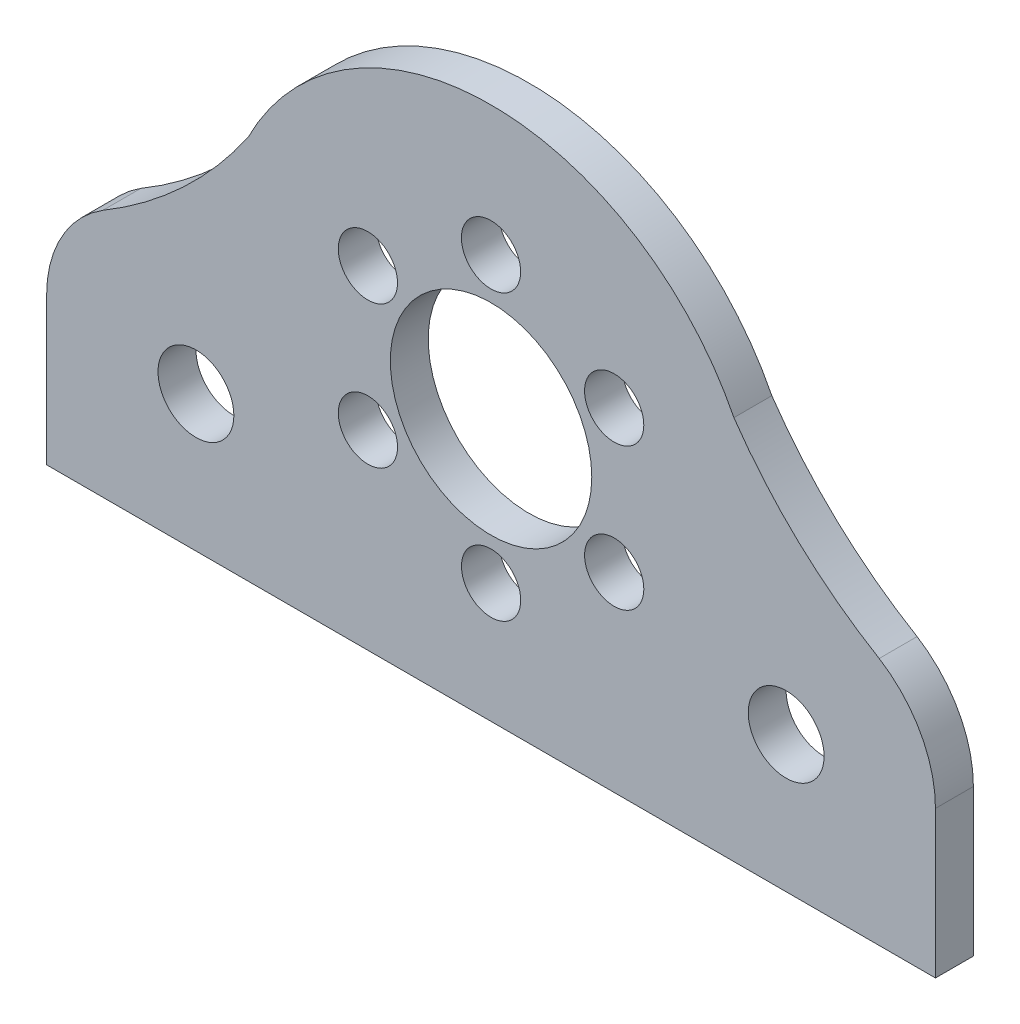
SolidWorks part; units mm, degrees
ref_plane "Alzado" through (0, 0, 0) normal (0, 0, 1) x (1, 0, 0)
ref_plane "Planta" through (0, 0, 0) normal (0, 1, 0) x (1, 0, 0)
ref_plane "Vista lateral" through (0, 0, 0) normal (1, 0, 0) x (0, 0, -1)
sketch "Croquis1" plane through (0, 0, 0) normal (0, 0, 1) x (1, 0, 0)
  line L4 (0, 0) -> (0, 1.5946) construction
  line L17 (-18.75, -11.05) -> (18.75, -11.05)
  line L18 (0, -11.05) -> (0, -9.9022) construction
  line L21 (-18.75, -11.05) -> (-18.75, -4.8527)
  line L23 (18.75, -11.05) -> (18.75, -4.8527)
  line L25 (0, 11.4788) -> (0, -11.05) construction
  circle A8 centre (0, 0) radius 4.25
  circle A12 centre (-0.0012, 5.9988) radius 1.25
  circle A13 centre (5.1945, 3.0004) radius 1.25
  circle A14 centre (5.1957, -2.9984) radius 1.25
  circle A15 centre (0.0012, -5.9988) radius 1.25
  circle A16 centre (-5.1945, -3.0004) radius 1.25
  circle A17 centre (-5.1957, 2.9984) radius 1.25
  circle A19 centre (12.45, -5.3) radius 1.6
  circle A21 centre (-12.45, -5.3) radius 1.6
  arc A23 (10.2473, 5.1727) -> (-10.2473, 5.1727) centre (0, 0) ccw
  arc A32 (-18.75, -4.8527) -> (-16.3755, -0.5624) centre (-13.6868, -4.8527) cw
  arc A33 (-16.3755, -0.5624) -> (-10.2473, 5.1727) centre (-26.2731, 16.1553) ccw
  arc A34 (16.3755, -0.5624) -> (10.2473, 5.1727) centre (26.2731, 16.1553) cw
  arc A35 (18.75, -4.8527) -> (16.3755, -0.5624) centre (13.6868, -4.8527) ccw
  point P29 (-11.465, -0.5624)
  point P34 (11.465, -0.5624)
  dimension "D1" = 12.45
  dimension "D2" = 37.5
  dimension "D7" = 3.2
  dimension "D4" = 5.3
  dimension "D5" = 11.05
  dimension "D6" = 8.5
  dimension "D3" = 2.5
  dimension "D9" = 11.4788
extrude "Saliente-Extruir1" add sketch "Croquis1" along normal blind 1.6
